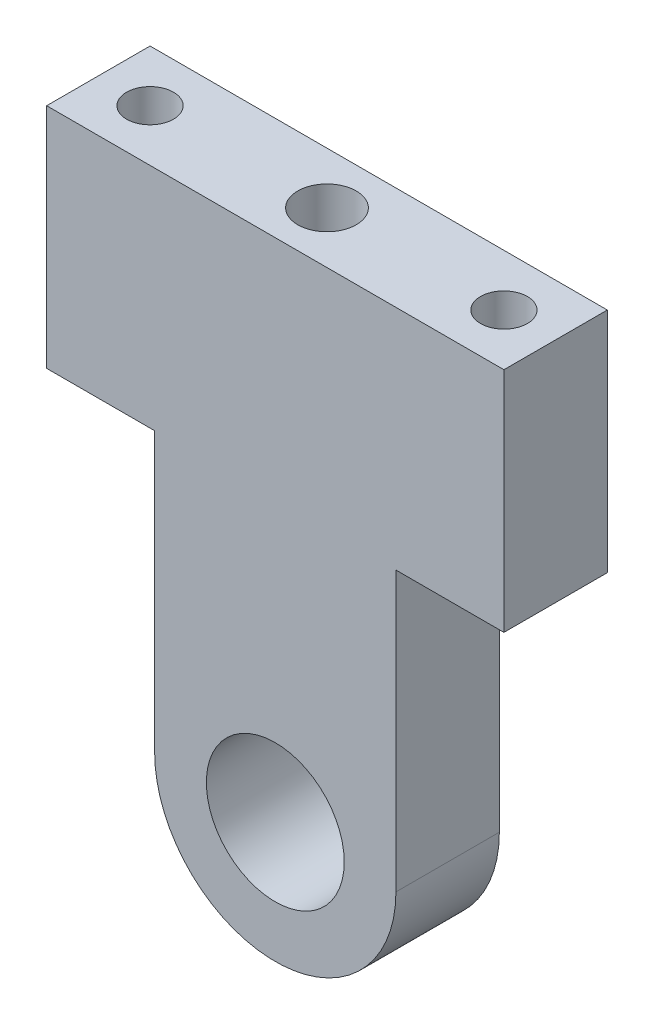
SolidWorks part; units mm, degrees
ref_plane "Front Plane" through (0, 0, 0) normal (0, 0, 1) x (1, 0, 0)
ref_plane "Top Plane" through (0, 0, 0) normal (0, 1, 0) x (1, 0, 0)
ref_plane "Right Plane" through (0, 0, 0) normal (1, 0, 0) x (0, 0, -1)
sketch "Sketch1" plane through (0, 0, 0) normal (0, 0, 1) x (1, 0, 0)
  line L0 (33.165, 33) -> (33.165, -40.4336) construction
  line L1 (0, 0) -> (66.33, 0) construction
  line L2 (0, 0) -> (0, 33)
  line L3 (0, 33) -> (66.33, 33)
  line L4 (66.33, 0) -> (66.33, 33)
  line L5 (15.665, 0) -> (50.665, 0) construction
  line L6 (15.665, 0) -> (15.665, -40.4336)
  line L7 (15.665, -40.4336) -> (50.665, -40.4336) construction
  line L8 (50.665, 0) -> (50.665, -40.4336)
  line L9 (0, 0) -> (15.665, 0)
  line L10 (50.665, 0) -> (66.33, 0)
  arc A0 (15.665, -40.4336) -> (50.665, -40.4336) centre (33.165, -40.4336) ccw
  circle A1 centre (33.165, -40.4336) radius 10
  point P9 (33.165, -40.4336)
  point P13 (0, 0)
  point P14 (0, 0)
  point P15 (0, 0)
  point P16 (0, 0)
  point P17 (16.7154, -36.8026)
  point P18 (0, 0)
  point P19 (0, 0)
  point P20 (0, 0)
  point P22 (16.7671, -22.5354)
  point P24 (0, 0)
  point P25 (16.7154, -36.8026)
  dimension "D5" = 20
  dimension "D1" = 66.33
  dimension "D2" = 33
  dimension "D3" = 35
extrude "Boss-Extrude1" add sketch "Sketch1" along normal blind 15
sketch "Sketch2" plane through (0, 33, 0) normal (0, 1, 0) x (1, 0, 0)
  line L0 (66.33, 0) -> (0, 0) construction
  line L1 (33.165, 0) -> (33.165, -15) construction
  line L2 (66.33, -15) -> (0, -15) construction
  line L3 (58.831, 0) -> (58.831, -15) construction
  circle A0 centre (33.165, -7.5) radius 4.25 construction
  circle A1 centre (58.831, -7.5) radius 3.4
  circle A2 centre (7.499, -7.5) radius 3.4
  dimension "D2" = 8.5
  dimension "D3" = 6.8
  dimension "D1" = 25.666
extrude "Cut-Extrude1" cut sketch "Sketch2" against normal blind 54
sketch "Sketch3" plane through (0, 33, 0) normal (0, 1, 0) x (1, 0, 0)
  circle A0 centre (33.165, -7.5) radius 4.25
extrude "Cut-Extrude2" cut sketch "Sketch3" against normal blind 28
